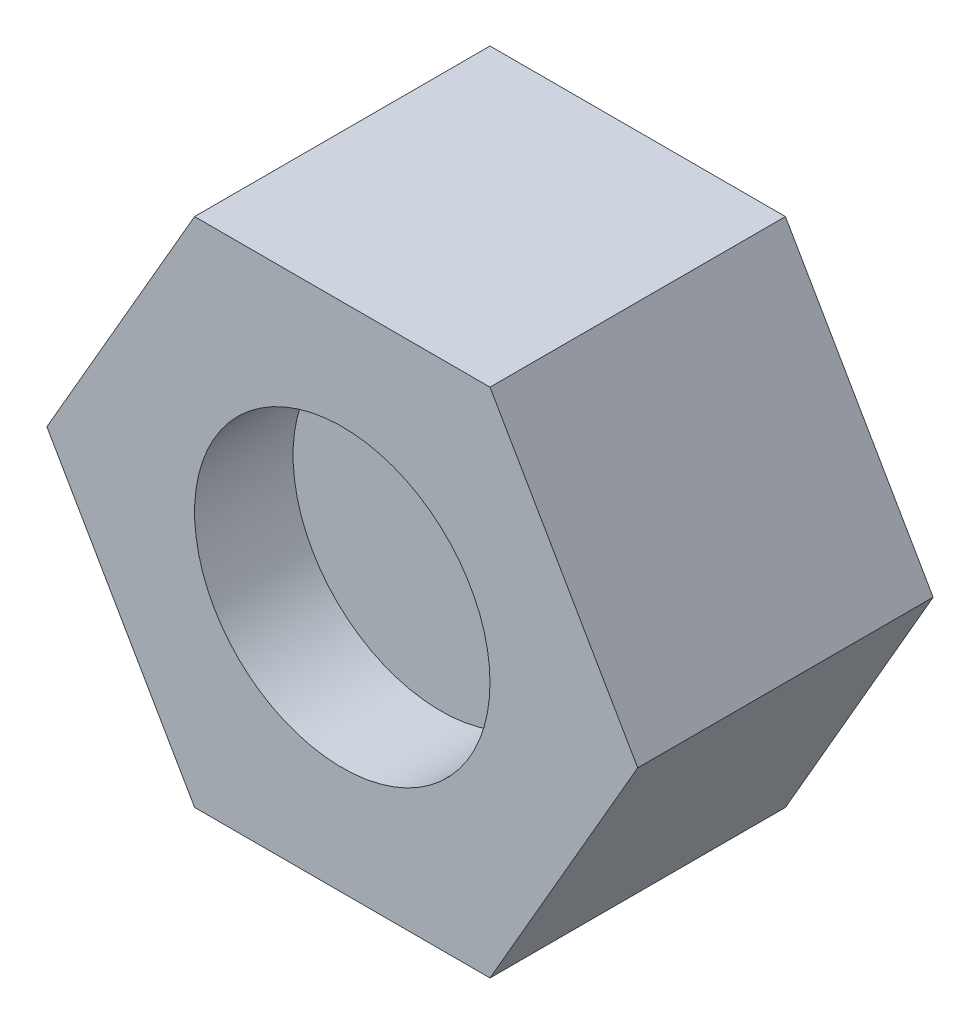
SolidWorks part; units mm, degrees
material "AISI 1020"
ref_plane "Front Plane" through (0, 0, 0) normal (0, 0, 1) x (1, 0, 0)
ref_plane "Top Plane" through (0, 0, 0) normal (0, 1, 0) x (1, 0, 0)
ref_plane "Right Plane" through (0, 0, 0) normal (1, 0, 0) x (0, 0, -1)
sketch "Sketch1" plane through (0, 0, 0) normal (0, 0, 1) x (1, 0, 0)
  line L1 (7.5, -12.9904) -> (15, 0)
  line L2 (15, 0) -> (7.5, 12.9904)
  line L3 (7.5, 12.9904) -> (-7.5, 12.9904)
  line L4 (-7.5, 12.9904) -> (-15, 0)
  line L5 (-15, 0) -> (-7.5, -12.9904)
  line L6 (-7.5, -12.9904) -> (7.5, -12.9904)
  circle A0 centre (0, 0) radius 12.9904 construction
  point P1 (0, 12.9904)
  dimension "D2" = 15
extrude "Boss-Extrude1" add sketch "Sketch1" along normal blind 15
sketch "Sketch2" plane through (0, 0, 15) normal (0, 0, 1) x (1, 0, 0)
  circle A0 centre (0, 0) radius 7.5
  dimension "D1" = 15
extrude "Cut-Extrude1" cut sketch "Sketch2" against normal blind 5
